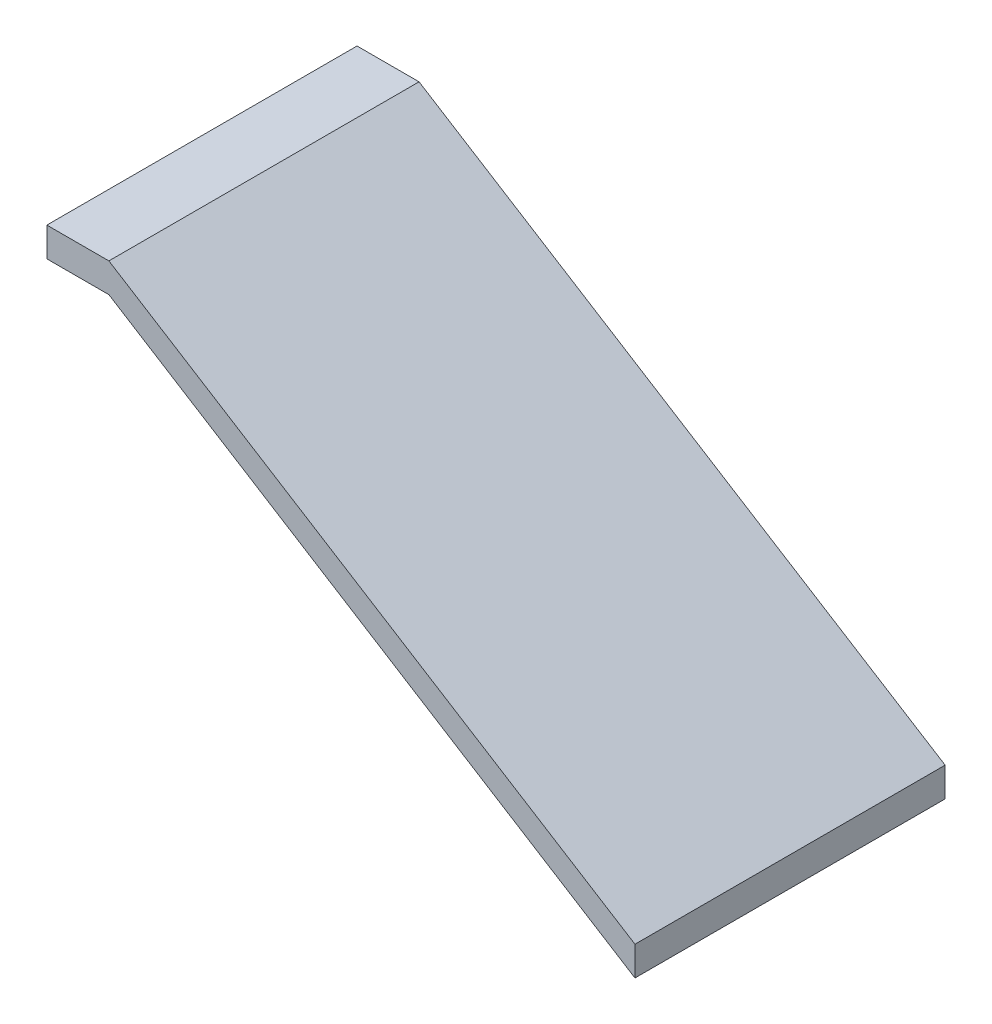
SolidWorks part; units mm, degrees
ref_plane "前视基准面" through (0, 0, 0) normal (0, 0, 1) x (1, 0, 0)
ref_plane "上视基准面" through (0, 0, 0) normal (0, 1, 0) x (1, 0, 0)
ref_plane "右视基准面" through (0, 0, 0) normal (1, 0, 0) x (0, 0, -1)
other "Configuration Table"
sketch "草图1" plane through (0, 0, 0) normal (0, 0, 1) x (1, 0, 0)
  line L0 (50, 562.7521) -> (150, 562.7521)
  line L1 (150, 562.7521) -> (998.0481, 32.8329)
  line L2 (998.0481, 32.8329) -> (998.0481, 80)
  line L3 (998.0481, 80) -> (150, 609.9193)
  line L4 (150, 609.9193) -> (50, 609.9193)
  line L5 (50, 609.9193) -> (50, 562.7521)
extrude "Compacted_low_permeability_bed_normal_40" add sketch "草图1" along normal blind 500 separate body
